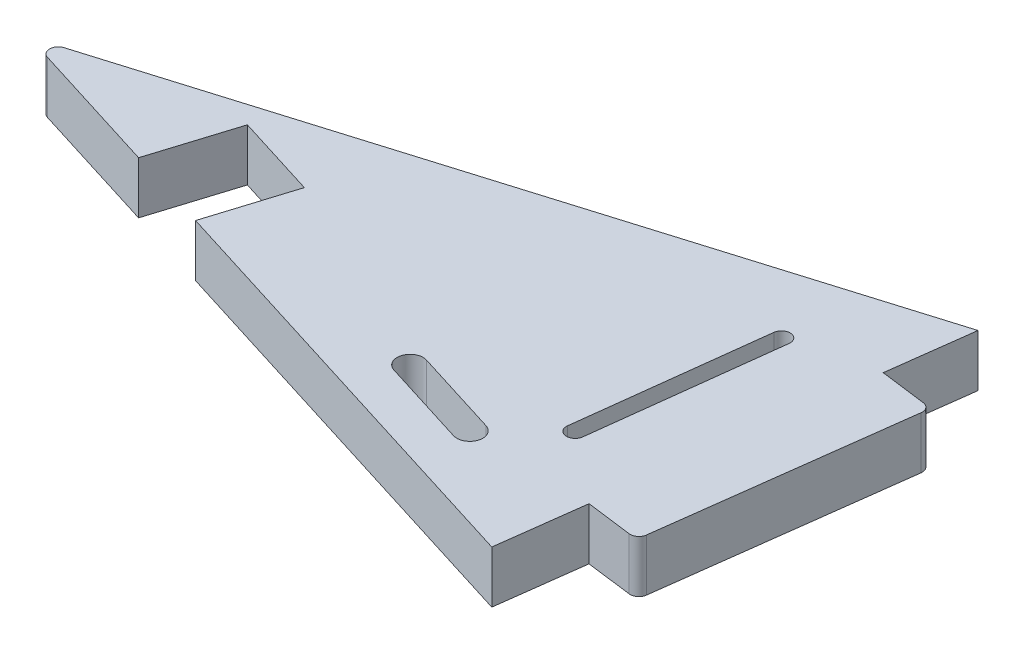
SolidWorks part; units mm, degrees
material "Balsa"
ref_plane "Front Plane" through (0, 0, 0) normal (0, 0, 1) x (1, 0, 0)
ref_plane "Top Plane" through (0, 0, 0) normal (0, 1, 0) x (1, 0, 0)
ref_plane "Right Plane" through (0, 0, 0) normal (1, 0, 0) x (0, 0, -1)
sketch "Sketch1" plane through (0, 0, 0) normal (0, 1, 0) x (1, 0, 0)
  line L0 (-2.5866, -0.183) -> (-1.3066, 9.7348)
  line L1 (3.8134, 49.4057) -> (-80.123, 24.0471)
  line L2 (-80.123, 24.0471) -> (-50.5622, 14.8094)
  line L3 (2.5652, 39.7347) -> (8.8628, 38.922)
  line L4 (8.8628, 38.922) -> (4.9911, 8.922)
  line L5 (4.9911, 8.922) -> (-1.3066, 9.7348)
  line L6 (2.5652, 39.7347) -> (3.8134, 49.4057)
  line L7 (-50.5622, 14.8094) -> (-49.2822, 24.7271) construction
  line L8 (-49.2822, 24.7271) -> (-39.3645, 23.4471) construction
  line L9 (-39.3645, 23.4471) -> (-40.8702, 11.7806) construction
  line L10 (-40.8702, 11.7806) -> (-2.5866, -0.183)
  line L11 (-6.7585, 37.3511) -> (-9.3198, 16.1487) construction
  line L12 (-5.7657, 37.2312) -> (-8.327, 16.0287)
  line L13 (-7.7512, 37.471) -> (-10.3126, 16.2686)
  line L14 (-50.5622, 14.8094) -> (-40.8702, 11.7806)
  arc A0 (-5.7657, 37.2312) -> (-7.7512, 37.471) centre (-6.7585, 37.3511) ccw
  arc A1 (-10.3126, 16.2686) -> (-8.327, 16.0287) centre (-9.3198, 16.1487) ccw
  point P11 (-1.9466, 4.7759)
  point P12 (-8.0391, 26.7499)
  dimension "D1" = 50
  dimension "D2" = 80
  dimension "D3" = 80
  dimension "D4" = 6.3498
  dimension "D5" = 30
  dimension "D6" = 6.35
  dimension "D7" = 10
  dimension "D8" = 10
  dimension "D9" = 10
  dimension "D10" = 39.5
  dimension "D11" = 1
extrude "Boss-Extrude1" add sketch "Sketch1" along normal blind 6
fillet "Fillet1" radius 1 3 edges at (4.9911, 3, -8.922) (8.8628, 3, -38.922) (-80.123, 3, -24.0471)
sketch "Sketch2" plane through (0, 6, 0) normal (0, 1, 0) x (1, 0, 0)
  line L0 (-61.7453, 18.3041) -> (-58.7625, 27.8489)
  line L1 (-58.7625, 27.8489) -> (-49.2177, 24.8662)
  line L2 (-49.2177, 24.8662) -> (-52.2005, 15.3214)
  line L3 (-61.7453, 18.3041) -> (-52.2005, 15.3214)
  line L4 (-77.017, 23.0765) -> (-2.5866, -0.183) construction
  line L5 (-25.4486, 13.2734) -> (-15.4486, 10.1484) construction
  line L6 (-25.0012, 14.7051) -> (-15.0012, 11.5801)
  line L7 (-25.896, 11.8417) -> (-15.896, 8.7167)
  arc A0 (-25.0012, 14.7051) -> (-25.896, 11.8417) centre (-25.4486, 13.2734) ccw
  arc A1 (-15.896, 8.7167) -> (-15.0012, 11.5801) centre (-15.4486, 10.1484) ccw
  point P9 (-20.4486, 11.7109)
  dimension "D5" = 1.5
  dimension "D1" = 10
  dimension "D2" = 10
  dimension "D3" = 16
  dimension "D4" = 10
extrude "Cut-Extrude1" cut sketch "Sketch2" against normal through all
